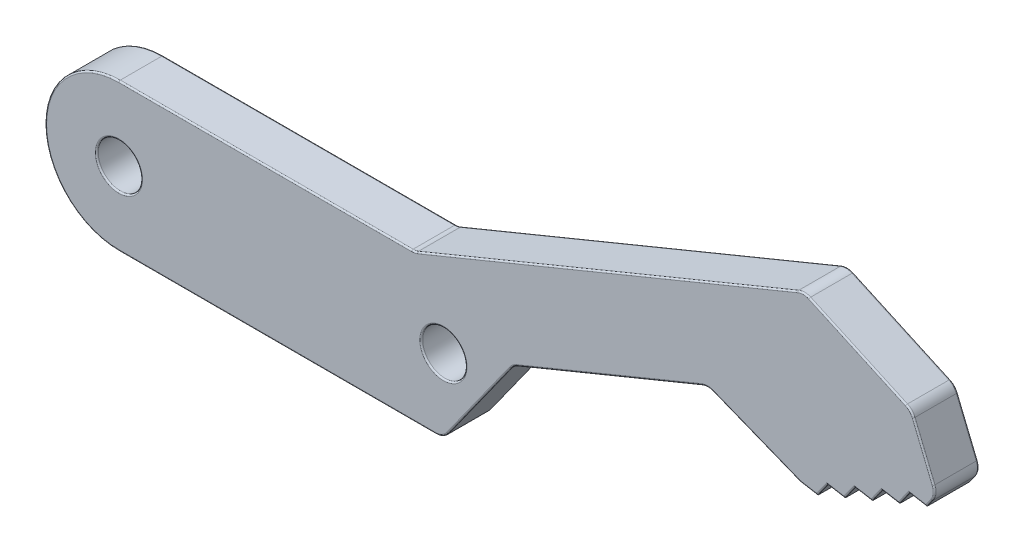
SolidWorks part; units mm, degrees
ref_plane "Front Plane" through (0, 0, 0) normal (0, 0, 1) x (1, 0, 0)
ref_plane "Top Plane" through (0, 0, 0) normal (0, 1, 0) x (1, 0, 0)
ref_plane "Right Plane" through (0, 0, 0) normal (1, 0, 0) x (0, 0, -1)
sketch "Sketch1" plane through (0, 0, 0) normal (0, 0, 1) x (1, 0, 0)
  line L0 (0, 0) -> (22, 0) construction
  line L1 (0, 5) -> (22, 5)
  line L2 (0, -5) -> (22, -5)
  line L3 (20.05, 5) -> (23.9914, -4.5863) construction
  line L4 (20.05, 5) -> (51.4959, 17.929) construction
  line L5 (23.9914, -4.5863) -> (55.4373, 8.3426) construction
  line L6 (51.4959, 17.929) -> (55.4373, 8.3426) construction
  line L7 (20.05, 5) -> (46.409, 15.8375)
  line L8 (46.409, 15.8375) -> (53.7261, 12.5046)
  line L9 (53.7261, 12.5046) -> (55.4373, 8.3426)
  line L10 (55.4373, 8.3426) -> (46.1885, 4.54) construction
  line L11 (46.1885, 4.54) -> (39.9002, 7.0361)
  line L12 (39.9002, 7.0361) -> (26.7299, 1.6211)
  line L13 (46.1885, 4.54) -> (47.3529, 4.3376)
  line L14 (47.3529, 4.3376) -> (48.0382, 5.3005)
  line L15 (47.3529, 4.3376) -> (54.752, 7.3797) construction
  line L16 (48.0382, 5.3005) -> (49.2027, 5.0981)
  line L17 (49.2027, 5.0981) -> (49.888, 6.0611)
  line L18 (49.888, 6.0611) -> (51.0524, 5.8587)
  line L19 (51.0524, 5.8587) -> (51.7378, 6.8216)
  line L20 (51.7378, 6.8216) -> (52.9022, 6.6192)
  line L21 (52.9022, 6.6192) -> (53.5875, 7.5821)
  line L22 (53.5875, 7.5821) -> (54.752, 7.3797)
  line L23 (54.752, 7.3797) -> (55.4373, 8.3426)
  line L24 (26.7299, 1.6211) -> (22, -5)
  arc A0 (0, 5) -> (0, -5) centre (0, 0) ccw
  arc A1 (22, -5) -> (22, 5) centre (22, 0) ccw
  circle A2 centre (0, 0) radius 1.5
  circle A3 centre (22, 0) radius 1.5
  point P3 (11, 0)
  dimension "D11" = 3
  dimension "D1" = 10
  dimension "D2" = 22
  dimension "D3" = 157.65
  dimension "D4" = 1.95
  dimension "D5" = 34
  dimension "D6" = 14.24
  dimension "D7" = 10
  dimension "D8" = 4.5
  dimension "D9" = 5.5
  dimension "D10" = 136
  dimension "D12" = 2
  dimension "D13" = 0.63
  dimension "D14" = 8
extrude "Boss-Extrude1" add sketch "Sketch1" along normal blind 3 contours A1 L1 A0 L2 A3 A2 | A1 L12 L11 L13 L14 L16 L17 L18 L19 L20 L21 L22 L23 L9 L8 L7 L1
fillet "Fillet1" radius 1 8 edges at (46.1885, 4.54, 1.5) (55.4373, 8.3426, 1.5) (53.7261, 12.5046, 1.5) (46.409, 15.8375, 1.5) (20.05, 5, 1.5) (26.7299, 1.6211, 1.5) (39.9002, 7.0361, 1.5) (22, -5, 1.5)
fillet "Fillet2" radius 0.1 58 edges at (47.6956, 4.8191, 0) (48.6205, 5.1993, 0) (49.5453, 5.5796, 0) (50.4702, 5.9599, 0) (51.3951, 6.3401, 0) (52.32, 6.7204, 0) (53.2449, 7.1006, 0) (54.1697, 7.4809, 0) (54.9346, 7.6363, 0) (55.296, 8.3588, 0) (54.5519, 10.4959, 0) (53.6718, 12.4523, 0) (50.0847, 14.1633, 0) (46.4074, 15.7477, 0) (33.1206, 10.374, 0) (20.0463, 5.019, 0) (9.9262, 5, 0) (-5, 0, 0) (10.7427, -5, 0) (21.943, -4.8892, 0) (24.4309, -1.5972, 0) (26.7551, 1.5893, 0) (33.2613, 4.3065, 0) (39.9006, 6.9575, 0) (43.1841, 5.7326, 0) (46.1899, 4.5451, 0) (46.8216, 4.43, 0) (1.5, 0, 0) (23.5, 0, 0) (39.9006, 6.9575, 3) (33.2613, 4.3065, 3) (26.7551, 1.5893, 3) (24.4309, -1.5972, 3) (21.943, -4.8892, 3) (10.7427, -5, 3) (-5, 0, 3) (9.9262, 5, 3) (20.0463, 5.019, 3) (33.1206, 10.374, 3) (46.4074, 15.7477, 3) (50.0847, 14.1633, 3) (53.6718, 12.4523, 3) (54.5519, 10.4959, 3) (55.296, 8.3588, 3) (54.9346, 7.6363, 3) (54.1697, 7.4809, 3) (53.2449, 7.1006, 3) (52.32, 6.7204, 3) (51.3951, 6.3401, 3) (50.4702, 5.9599, 3) (49.5453, 5.5796, 3) (48.6205, 5.1993, 3) (47.6956, 4.8191, 3) (46.8216, 4.43, 3) (46.1899, 4.5451, 3) (43.1841, 5.7326, 3) (1.5, 0, 3) (23.5, 0, 3)
